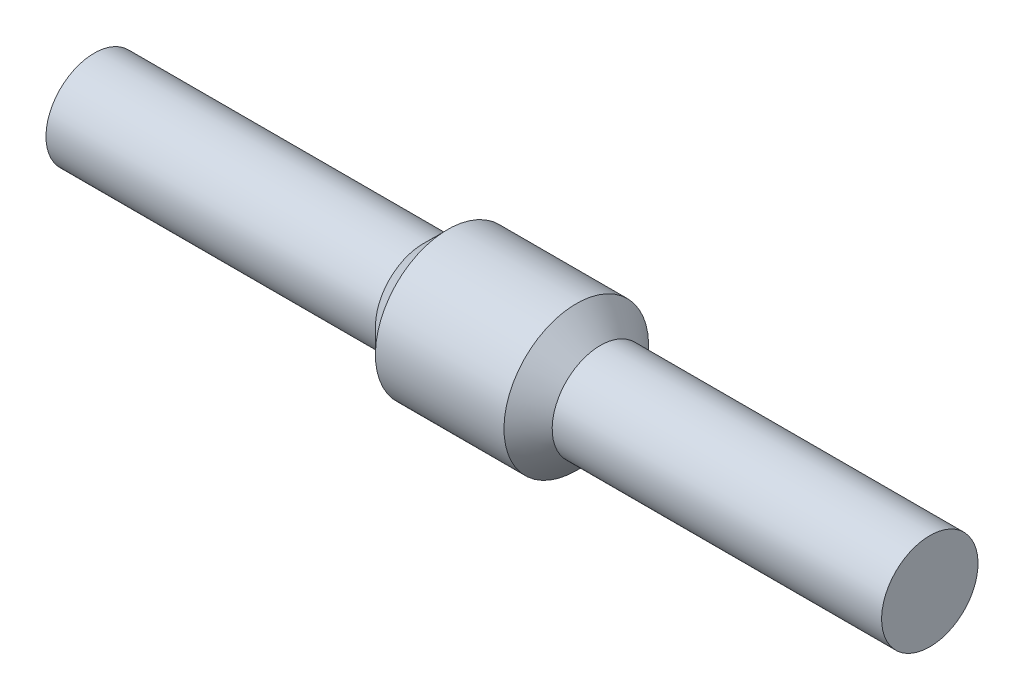
SolidWorks part; units mm, degrees
ref_plane "Front Plane" through (0, 0, 0) normal (0, 0, 1) x (1, 0, 0)
ref_plane "Top Plane" through (0, 0, 0) normal (0, 1, 0) x (1, 0, 0)
ref_plane "Right Plane" through (0, 0, 0) normal (1, 0, 0) x (0, 0, -1)
sketch "Sketch1" plane through (0, 0, 0) normal (0, 0, 1) x (1, 0, 0)
  line L0 (-14.928, 0) -> (21.0868, 0) construction
  line L1 (-13, 0) -> (-13, 1.5)
  line L2 (-13, 1.5) -> (-2.75, 1.5)
  line L3 (-2.75, 1.5) -> (-2, 2.25)
  line L4 (-2, 2.25) -> (2, 2.25)
  line L5 (2, 2.25) -> (2.75, 1.5)
  line L6 (2.75, 1.5) -> (13, 1.5)
  line L7 (13, 1.5) -> (13, 0)
  line L8 (0, 6.8309) -> (0, -4.0519) construction
  line L9 (-2.75, 1.5) -> (2.75, 1.5) construction
  line L10 (-13, 0) -> (13, 0)
  point P11 (0, 2.25)
  dimension "D1" = 26
  dimension "D2" = 3
  dimension "D3" = 4.5
  dimension "D4" = 4
revolve "Revolve1" add sketch "Sketch1" angle 360 about L10
